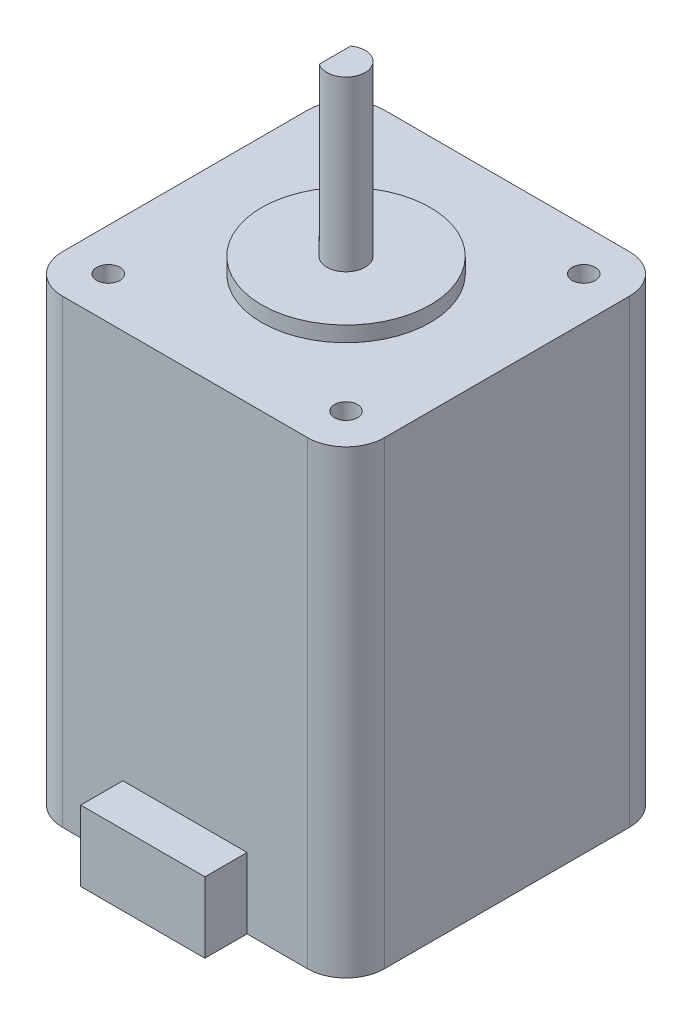
SolidWorks part; units mm, degrees
ref_plane "前视基准面" through (0, 0, 0) normal (0, 0, 1) x (1, 0, 0)
ref_plane "上视基准面" through (0, 0, 0) normal (0, 1, 0) x (1, 0, 0)
ref_plane "右视基准面" through (0, 0, 0) normal (1, 0, 0) x (0, 0, -1)
sketch "草图1" plane through (0, 0, 0) normal (0, 1, 0) x (1, 0, 0)
  line L1 (-21, 21) -> (21, 21)
  line L2 (-21, 21) -> (-21, -21)
  line L3 (-21, -21) -> (21, -21)
  line L4 (21, 21) -> (21, -21)
  line L5 (-21, 21) -> (21, -21) construction
  line L6 (-21, -21) -> (21, 21) construction
  point P0 (0, 0)
  dimension "D1" = 42
extrude "凸台-拉伸1" add sketch "草图1" along normal blind 60
sketch "草图2" plane through (0, 60, 0) normal (0, 1, 0) x (1, 0, 0)
  circle A0 centre (0, 0) radius 11
  dimension "D1" = 22
extrude "凸台-拉伸2" add sketch "草图2" along normal blind 2
sketch "草图3" plane through (0, 62, 0) normal (0, 1, 0) x (1, 0, 0)
  circle A0 centre (0, 0) radius 2.5
  dimension "D1" = 5
extrude "凸台-拉伸3" add sketch "草图3" along normal blind 22
sketch "草图5" plane through (0, 0, 21) normal (0, 0, 1) x (1, 0, 0)
  line L0 (-21, 0) -> (21, 0) construction
  line L1 (-8.1, 9.2) -> (8.1, 9.2)
  line L2 (-8.1, 9.2) -> (-8.1, 0)
  line L3 (-8.1, 0) -> (8.1, 0)
  line L4 (8.1, 9.2) -> (8.1, 0)
  line L5 (-8.1, 9.2) -> (8.1, 0) construction
  line L6 (-8.1, 0) -> (8.1, 9.2) construction
  point P0 (0, 4.6)
  dimension "D1" = 9.2
  dimension "D2" = 16.2
extrude "凸台-拉伸4" add sketch "草图5" along normal blind 5.5
sketch "草图6" plane through (0, 60, 0) normal (0, 1, 0) x (1, 0, 0)
  line L0 (-21, 21) -> (21, -21) construction
  line L1 (21, 21) -> (-21, -21) construction
  line L2 (0, 0) -> (40.1341, 0) construction
  circle A0 centre (-15.5, 15.5) radius 1.5
  circle A2 centre (15.5, 15.5) radius 1.5
  circle A3 centre (15.5, -15.5) radius 1.5
  circle A4 centre (-15.5, -15.5) radius 1.5
  point P23 (0, 0)
  dimension "D1" = 3
  dimension "D2" = 15.5
  dimension "D3" = 4
extrude "切除-拉伸1" cut sketch "草图6" against normal blind 5
fillet "圆角1" radius 5 4 edges at (21, 30, -21) (-21, 30, -21) (21, 30, 21) (-21, 30, 21)
sketch "草图7" plane through (0, 0, 0) normal (0, -1, 0) x (1, 0, 0)
  circle A0 centre (0, 0) radius 4
  dimension "D1" = 8
extrude "切除-拉伸2" cut sketch "草图7" against normal blind 5
sketch "草图8" plane through (0, 84, 0) normal (0, 1, 0) x (1, 0, 0)
  line L0 (-1.4382, 2.0449) -> (-1.4382, -2.0449)
  circle A0 centre (0, 0) radius 2.5 construction
  circle A1 centre (0, 0) radius 2.5 construction
  circle A2 centre (0, 0) radius 2.5
  circle M2 centre (0, 0) radius 2.5
extrude "切除-拉伸3" cut sketch "草图8" against normal blind 20 contours L0 M2
